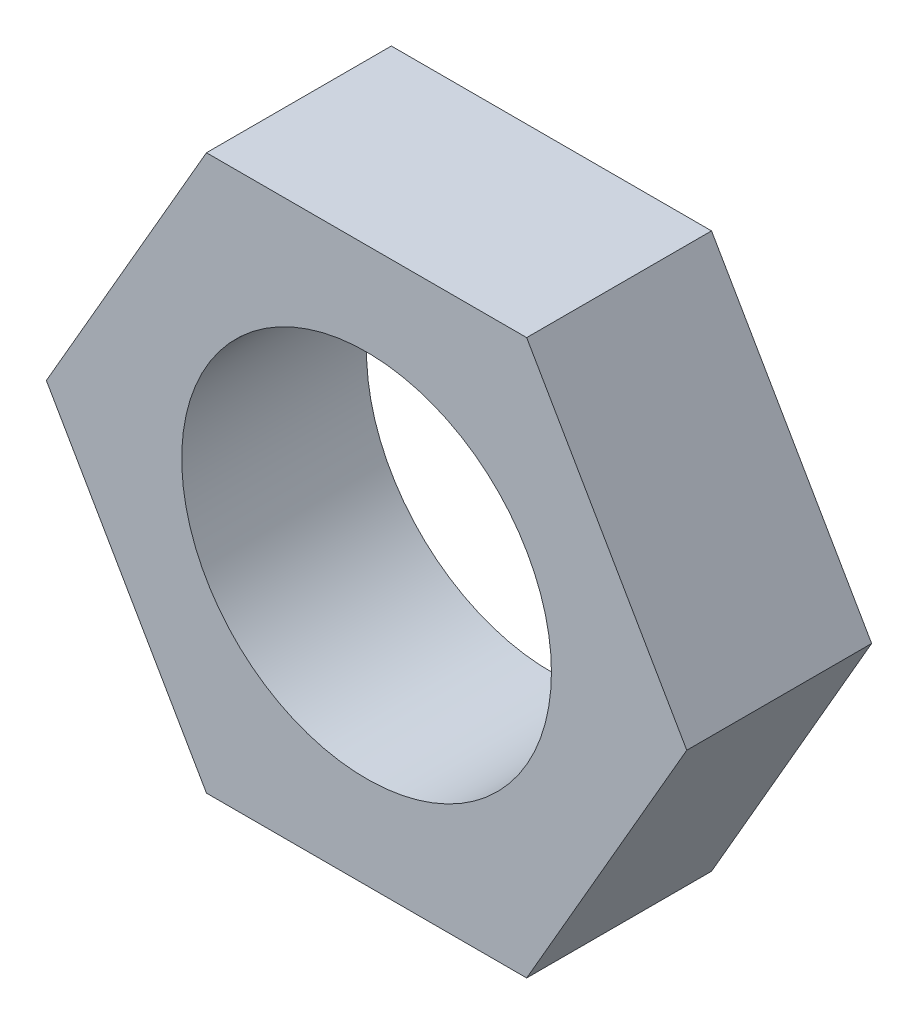
SolidWorks part; units mm, degrees
ref_plane "정면" through (0, 0, 0) normal (0, 0, 1) x (1, 0, 0)
ref_plane "윗면" through (0, 0, 0) normal (0, 1, 0) x (1, 0, 0)
ref_plane "우측면" through (0, 0, 0) normal (1, 0, 0) x (0, 0, -1)
sketch "스케치1" plane through (0, 0, 0) normal (0, 0, 1) x (1, 0, 0)
  line L1 (3.4641, 0) -> (1.7321, 3)
  line L2 (1.7321, 3) -> (-1.7321, 3)
  line L3 (-1.7321, 3) -> (-3.4641, 0)
  line L4 (-3.4641, 0) -> (-1.7321, -3)
  line L5 (-1.7321, -3) -> (1.7321, -3)
  line L6 (1.7321, -3) -> (3.4641, 0)
  circle A0 centre (0, 0) radius 3 construction
  circle A1 centre (0, 0) radius 2
  dimension "D2" = 4
  dimension "D1" = 6
extrude "보스-돌출1" add sketch "스케치1" along normal blind 2
